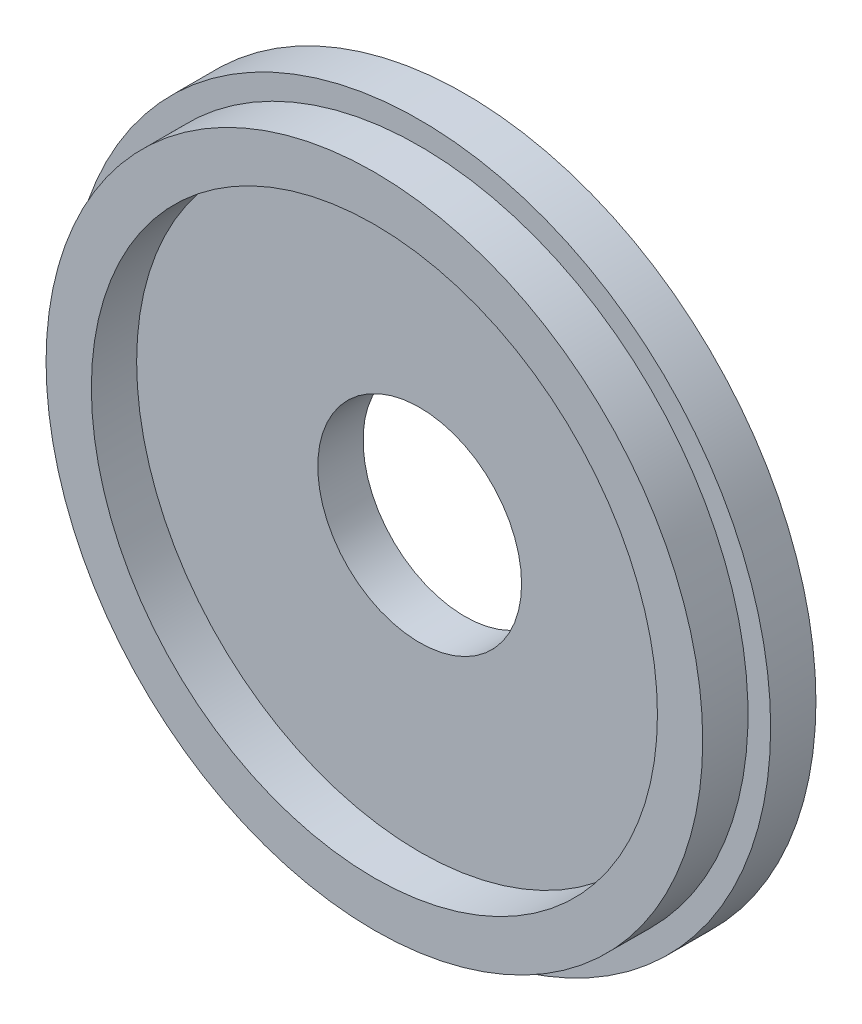
SolidWorks part; units mm, degrees
ref_plane "Front Plane" through (0, 0, 0) normal (0, 0, 1) x (1, 0, 0)
ref_plane "Top Plane" through (0, 0, 0) normal (0, 1, 0) x (1, 0, 0)
ref_plane "Right Plane" through (0, 0, 0) normal (1, 0, 0) x (0, 0, -1)
sketch "Sketch1" plane through (0, 0, 0) normal (0, 0, 1) x (1, 0, 0)
  circle A0 centre (0, 0) radius 14.5
  dimension "D1" = 29
extrude "Boss-Extrude1" add sketch "Sketch1" along normal blind 2
sketch "Sketch2" plane through (0, 0, 2) normal (0, 0, 1) x (1, 0, 0)
  circle A0 centre (0, 0) radius 14.5 construction
  circle A1 centre (0, 0) radius 14.5
  circle A2 centre (0, 0) radius 12.5
  dimension "D1" = 2
extrude "Boss-Extrude2" add sketch "Sketch2" along normal blind 2
sketch "Sketch3" plane through (0, 0, 2) normal (0, 0, 1) x (1, 0, 0)
  circle A0 centre (0, 0) radius 4.5
  dimension "D1" = 9
extrude "Cut-Extrude1" cut sketch "Sketch3" against normal blind 2
sketch "Sketch4" plane through (0, 0, 0) normal (0, 0, -1) x (-1, 0, 0)
  circle A0 centre (0, 0) radius 14.5 construction
  circle A1 centre (0, 0) radius 14.5
  circle A2 centre (0, 0) radius 15.5
  dimension "D1" = 1
extrude "Boss-Extrude3" add sketch "Sketch4" against normal blind 2
